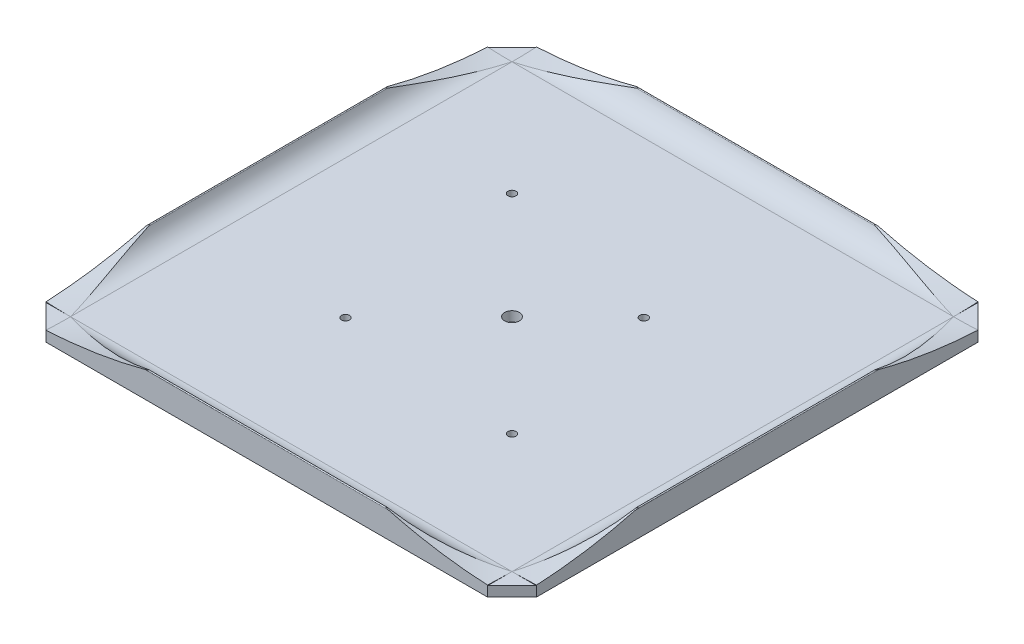
SolidWorks part; units mm, degrees
ref_plane "前视基准面" through (0, 0, 0) normal (0, 0, 1) x (1, 0, 0)
ref_plane "上视基准面" through (0, 0, 0) normal (0, 1, 0) x (1, 0, 0)
ref_plane "右视基准面" through (0, 0, 0) normal (1, 0, 0) x (0, 0, -1)
sketch "草图1" plane through (0, 0, 0) normal (0, 1, 0) x (1, 0, 0)
  line L1 (-100, 100) -> (100, 100)
  line L2 (-100, 100) -> (-100, -100)
  line L3 (-100, -100) -> (100, -100)
  line L4 (100, 100) -> (100, -100)
  line L5 (-100, 100) -> (100, -100) construction
  line L6 (-100, -100) -> (100, 100) construction
  circle A0 centre (0, 0) radius 3
  circle A1 centre (27.2236, 26.5165) radius 1.65
  circle A2 centre (-43.4871, 43.4871) radius 1.65
  circle A3 centre (-33.5876, -34.2947) radius 1.65
  circle A4 centre (41.3657, -41.3657) radius 1.65
  point P0 (0, 0)
  dimension "D3" = 6
  dimension "D4" = 3.3
  dimension "D1" = 200
  dimension "D2" = 200
extrude "凸台-拉伸1" add sketch "草图1" along normal blind 4
sketch "草图3" plane through (0, 0, 0) normal (1, 0, 0) x (0, 0, -1)
  line L0 (-100, 4) -> (-90, 4)
  line L1 (-100, 4) -> (-100, 10.5359)
  line L2 (0, 11.8078) -> (0, 91.7644) construction
  line L3 (-100, 14) -> (0, 14) construction
  line L4 (100, 4) -> (100, 10.5359)
  line L5 (100, 4) -> (90, 4)
  arc A0 (-99.4175, 10.6368) -> (-90, 4) centre (-90, 14) ccw
  arc A1 (-99.4175, 10.6368) -> (-100, 10.5359) centre (-99.7, 10.5359) ccw
  arc A2 (99.4175, 10.6368) -> (100, 10.5359) centre (99.7, 10.5359) cw
  arc A3 (99.4175, 10.6368) -> (90, 4) centre (90, 14) cw
  dimension "D2" = 10
  dimension "D3" = 0.3
  dimension "D1" = 10
extrude "凸台-拉伸3" add sketch "草图3" along normal mid plane 180
sketch "草图5" plane through (0, 0, 0) normal (0, 0, 1) x (1, 0, 0)
  line L0 (-100, 4) -> (-90, 4)
  line L1 (-100, 4) -> (-100, 10.5359)
  line L2 (0, 11.8078) -> (0, 91.7644) construction
  line L3 (-100, 14) -> (0, 14) construction
  line L4 (100, 4) -> (100, 10.5359)
  line L5 (100, 4) -> (90, 4)
  arc A0 (-99.4175, 10.6368) -> (-90, 4) centre (-90, 14) ccw
  arc A1 (-99.4175, 10.6368) -> (-100, 10.5359) centre (-99.7, 10.5359) ccw
  arc A2 (99.4175, 10.6368) -> (100, 10.5359) centre (99.7, 10.5359) cw
  arc A3 (99.4175, 10.6368) -> (90, 4) centre (90, 14) cw
  dimension "D2" = 10
  dimension "D3" = 0.3
  dimension "D1" = 10
extrude "凸台-拉伸4" add sketch "草图5" along normal mid plane 180
sketch "草图7" plane through (0, 0, 0) normal (0, 1, 0) x (1, 0, 0)
  line L0 (-100, 100) -> (100, -100) construction
  line L1 (-100, -100) -> (100, 100) construction
sketch "草图8" plane through (0, 0, 0) normal (0, 1, 0) x (1, 0, 0)
  line L0 (-100, 100) -> (-100, 90)
  line L1 (-100, 90) -> (-90, 100)
  line L2 (-90, 100) -> (-100, 100)
  line L3 (100, 90) -> (100, 100)
  line L4 (90, 100) -> (100, 90)
  line L5 (100, 100) -> (90, 100)
  line L6 (90, -100) -> (100, -100)
  line L7 (100, -90) -> (90, -100)
  line L8 (100, -100) -> (100, -90)
  line L9 (-100, -90) -> (-100, -100)
  line L10 (-90, -100) -> (-100, -90)
  line L11 (-100, -100) -> (-90, -100)
  point P18 (0, 0)
  dimension "D1" = 4
extrude "切除-拉伸1" cut sketch "草图8" along normal blind 10
sketch "草图9" plane through (95, 0, -95) normal (0.7071, 0, -0.7071) x (-0.7071, 0, -0.7071)
  line L0 (0, 0) -> (0, 33.6333) construction
  circle A0 centre (0, 104) radius 100
  dimension "D1" = 200
extrude "切除-拉伸2" cut sketch "草图9" against normal blind 70
pattern_circular "阵列(圆周)1" count 4 over 360 about axis through (0, 4, 0) along (0, -1, 0) of "切除-拉伸2"
